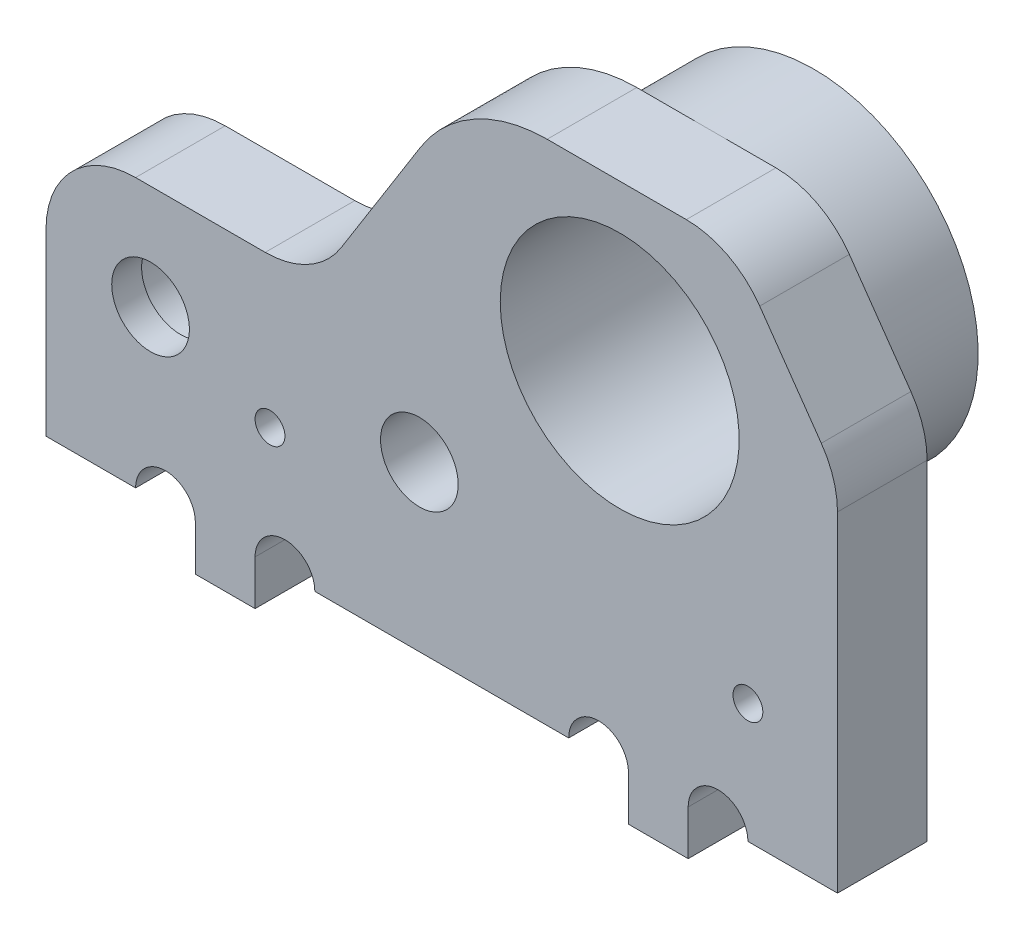
SolidWorks part; units mm, degrees
ref_plane "Front Plane" through (0, 0, 0) normal (0, 0, 1) x (1, 0, 0)
ref_plane "Top Plane" through (0, 0, 0) normal (0, 1, 0) x (1, 0, 0)
ref_plane "Right Plane" through (0, 0, 0) normal (1, 0, 0) x (0, 0, -1)
sketch "Sketch1" plane through (0, 0, 0) normal (0, 1, 0) x (1, 0, 0)
  line L1 (0, 0) -> (26.5, 0)
  line L2 (0, 0) -> (0, 6)
  line L3 (0, 6) -> (26.5, 6)
  line L4 (26.5, 0) -> (26.5, 6)
  dimension "D1" = 26.5
  dimension "D2" = 6
extrude "Boss-Extrude1" add sketch "Sketch1" along normal blind 17
ref_plane "Plane1" through (0, 5.5, 0) normal (0, 1, 0) x (1, 0, 0)
sketch "Sketch2" plane through (0, 0, 0) normal (0, 0, 1) x (1, 0, 0)
  line L0 (5.225, 5.5) -> (-5.225, 5.5) construction
  line L1 (26.5, 17) -> (26.5, 0) construction
  circle A0 centre (12.5, 5.5) radius 1.5
  circle A1 centre (12.5, 5.5) radius 9 construction
  dimension "D1" = 3
  dimension "D2" = 14
  dimension "D3" = 18
extrude "Cut-Extrude1" cut sketch "Sketch2" against normal blind 1
sketch "Sketch3" plane through (0, 0, -1) normal (0, 0, 1) x (1, 0, 0)
  circle A0 centre (12.5, 5.5) radius 1.3
  circle A1 centre (12.5, 5.5) radius 1.5 construction
  dimension "D1" = 0.2
extrude "Cut-Extrude2" cut sketch "Sketch3" against normal through all
sketch "Sketch4" plane through (0, 0, 0) normal (0, 0, 1) x (1, 0, 0)
  line L0 (5.225, 5.5) -> (-5.225, 5.5) construction
  circle A0 centre (19.2082, 11.5) radius 4
  circle A1 centre (12.5, 5.5) radius 1.5 construction
  dimension "D1" = 9
  dimension "D2" = 8
  dimension "D3" = 6
extrude "Cut-Extrude3" cut sketch "Sketch4" against normal through all
sketch "Sketch5" plane through (0, 0, 0) normal (0, 0, 1) x (1, 0, 0)
  line L0 (5.225, 5.5) -> (-5.225, 5.5) construction
  circle A0 centre (3.5, 5.5) radius 2.5
  circle A1 centre (12.5, 5.5) radius 1.5 construction
  dimension "D1" = 5
  dimension "D2" = 9
extrude "Cut-Extrude4" cut sketch "Sketch5" against normal blind 1.5
sketch "Sketch6" plane through (0, 0, -1.5) normal (0, 0, 1) x (1, 0, 0)
  circle A0 centre (3.5, 5.5) radius 1.5
  circle A1 centre (3.5, 5.5) radius 2.5 construction
  dimension "D1" = 3
extrude "Cut-Extrude8" cut sketch "Sketch6" against normal blind 1
sketch "Sketch7" plane through (0, 0, -2.5) normal (0, 0, 1) x (1, 0, 0)
  circle A0 centre (3.5, 5.5) radius 1.3
  circle A1 centre (3.5, 5.5) radius 1.5 construction
  dimension "D1" = 0.2
extrude "Cut-Extrude9" cut sketch "Sketch7" against normal through all
ref_plane "Plane2" through (0, 0, -9.3) normal (0, 0, -1) x (-1, 0, 0)
sketch "Sketch8" plane through (0, 0, -6) normal (0, 0, -1) x (-1, 0, 0)
  circle A0 centre (-3.5, 5.5) radius 2.5
  dimension "D1" = 5
extrude "Cut-Extrude10" cut sketch "Sketch8" against normal blind 1
sketch "Sketch9" plane through (0, 0, -5) normal (0, 0, -1) x (-1, 0, 0)
  circle A0 centre (-3.5, 5.5) radius 1.5
  dimension "D1" = 3
extrude "Cut-Extrude11" cut sketch "Sketch9" against normal blind 1
sketch "Sketch10" plane through (0, 0, -6) normal (0, 0, -1) x (-1, 0, 0)
  line L0 (-26.5, 17) -> (0, 17) construction
  circle A0 centre (-19.2082, 11.5) radius 5.5
  circle A1 centre (-19.2082, 11.5) radius 4 construction
  circle A2 centre (-19.2082, 11.5) radius 4
extrude "Boss-Extrude2" add sketch "Sketch10" along normal blind 3.5
sketch "Sketch11" plane through (0, 0, -6) normal (0, 0, -1) x (-1, 0, 0)
  circle A0 centre (-12.5, 5.5) radius 1.3 construction
  circle A1 centre (-12.5, 5.5) radius 1.3
  circle A2 centre (-12.5, 5.5) radius 3
  dimension "D1" = 6
extrude "Boss-Extrude4" add sketch "Sketch11" along normal blind 2
sketch "Sketch12" plane through (0, 0, -8) normal (0, 0, -1) x (-1, 0, 0)
  circle A0 centre (-12.5, 5.5) radius 1.5
  dimension "D1" = 3
extrude "Cut-Extrude12" cut sketch "Sketch12" against normal blind 1
sketch "Sketch17" plane through (0, 0, 0) normal (0, -1, 0) x (1, 0, 0)
  line L0 (10.175, 0) -> (-10.175, 0) construction
  line L1 (5, 0) -> (7, 0)
  line L2 (5, 0) -> (5, -6)
  line L3 (5, -6) -> (7, -6)
  line L4 (7, 0) -> (7, -6)
  line L5 (26.5, -6) -> (0, -6) construction
  line L6 (26.5, 0) -> (26.5, -6) construction
  line L7 (19.5, 0) -> (21.5, 0)
  line L8 (19.5, 0) -> (19.5, -6)
  line L9 (19.5, -6) -> (21.5, -6)
  line L10 (21.5, 0) -> (21.5, -6)
  line L11 (0, -5.236) -> (0, 5.236) construction
  dimension "D1" = 2
  dimension "D2" = 2
  dimension "D3" = 5
  dimension "D4" = 5
extrude "Boss-Extrude6" add sketch "Sketch17" along normal blind 1.5
sketch "Sketch18" plane through (0, 0, -6) normal (0, 0, -1) x (-1, 0, 0)
  line L0 (5.225, 0) -> (-5.225, 0) construction
  line L1 (-21.5, -1.5) -> (-21.5, 0) construction
  line L2 (-19.5, -1.5) -> (-19.5, 0) construction
  line L3 (-7, -1.5) -> (-7, 0) construction
  line L4 (-5, -1.5) -> (-5, 0) construction
  circle A0 centre (-22.5, 0) radius 1
  circle A1 centre (-18.5, 0) radius 1
  circle A2 centre (-8, 0) radius 1
  circle A3 centre (-4, 0) radius 1
  dimension "D1" = 2
extrude "Cut-Extrude17" cut sketch "Sketch18" against normal through all
chamfer "Chamfer2" distance 5 distance2 3.5 1 edges at (26.5, 17, -3)
fillet "Fillet11" radius 3 2 edges at (26.5, 12, -3) (23, 17, -3)
sketch "Sketch19" plane through (0, 0, -6) normal (0, 0, -1) x (-1, 0, 0)
  line L0 (-14.5471, 14.4196) -> (-9.9576, 7.0925)
  line L1 (-13.8002, 2.7964) -> (-21.5918, 6.5434)
  circle A0 centre (-12.5, 5.5) radius 3 construction
  circle A1 centre (-19.2082, 11.5) radius 5.5 construction
  arc A2 (-9.9576, 7.0925) -> (-13.8002, 2.7964) centre (-12.5, 5.5) ccw
  arc A3 (-21.5918, 6.5434) -> (-14.5471, 14.4196) centre (-19.2082, 11.5) ccw
extrude "Boss-Extrude7" add sketch "Sketch19" along normal up to surface (2 mm away) up to face at (11, 5.5, -8)
sketch "Sketch20" plane through (0, 0, -6) normal (0, 0, -1) x (-1, 0, 0)
  line L0 (5.225, 0) -> (-5.225, 0) construction
  line L1 (0, 17) -> (-14.011, 17)
  line L2 (0, 17) -> (0, 9)
  line L3 (0, 9) -> (-9, 9)
  line L5 (-9, 9) -> (-14.011, 17)
  line L6 (-19.2082, 17) -> (0, 17) construction
  line L7 (-9.9576, 7.0925) -> (-14.5471, 14.4196) construction
  dimension "D1" = 9
extrude "Cut-Extrude19" cut sketch "Sketch20" against normal through all
fillet "Fillet13" radius 5 1 edges at (14.011, 17, -3)
fillet "Fillet14" radius 3 1 edges at (9, 9, -3)
fillet "Fillet15" radius 3 1 edges at (0, 9, -3)
sketch "Skizze1" plane through (0, 0, -6) normal (0, 0, -1) x (-1, 0, 0)
  line L0 (5.225, 0) -> (-5.225, 0) construction
  line L1 (-26.5, 11.0543) -> (-26.5, 0) construction
  circle A0 centre (-23.5, 4) radius 0.5
  circle A1 centre (-7.5, 4) radius 0.5
  dimension "D1" = 1
  dimension "D2" = 1
  dimension "D3" = 4
  dimension "D4" = 16
  dimension "D5" = 3
extrude "Schnitt-Linear austragen1" cut sketch "Skizze1" against normal through all
ref_plane "Ebene1" through (0, 0, -3) normal (0, 0, -1) x (-1, 0, 0)
sketch "Skizze2" plane through (0, 5.5, 0) normal (0, 1, 0) x (1, 0, 0)
  line L0 (10.175, 3) -> (-10.175, 3) construction
  line L1 (26.5, 0) -> (0, 0)
  line L2 (26.5, 0) -> (26.5, 3)
  line L3 (26.5, 3) -> (0, 3)
  line L4 (0, 0) -> (0, 3)
  line L6 (26.5, 6) -> (26.5, 0) construction
  line L7 (0, -5.225) -> (0, 5.225) construction
  line L8 (-10.175, 0) -> (10.175, 0) construction
extrude "Schnitt-Linear austragen2" cut sketch "Skizze2" against normal through all both and the other way through all
